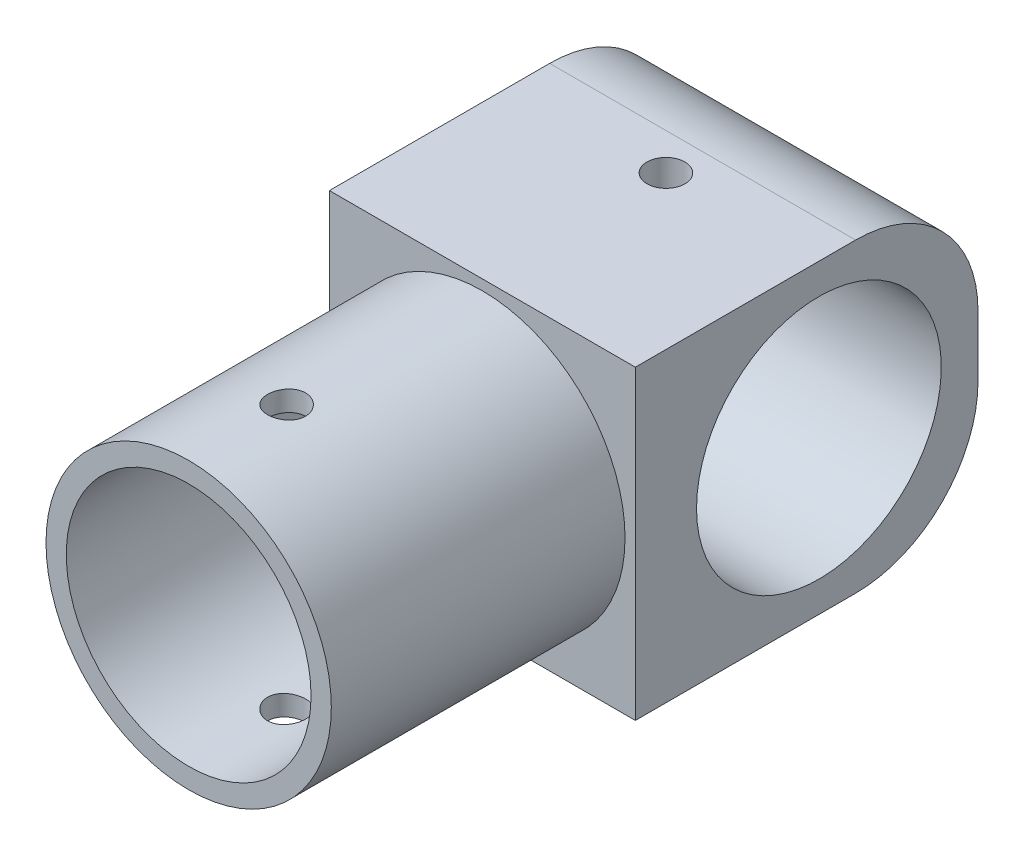
SolidWorks part; units mm, degrees
material "6061 合金"
ref_plane "前视基准面" through (0, 0, 0) normal (0, 0, 1) x (1, 0, 0)
ref_plane "上视基准面" through (0, 0, 0) normal (0, 1, 0) x (1, 0, 0)
ref_plane "右视基准面" through (0, 0, 0) normal (1, 0, 0) x (0, 0, -1)
other "Configuration Table"
ref_plane "基准面1" through (0, -5.2507, 0) normal (0, -1, 0) x (1, 0, 0)
sketch "草图1" plane through (0, -5.2507, 0) normal (0, -1, 0) x (1, 0, 0)
  line L0 (-8.6144, 0) -> (-8.6144, -28)
  line L1 (-8.6144, -28) -> (16.3856, -28)
  line L2 (16.3856, -28) -> (16.3856, 0)
  line L3 (16.3856, 0) -> (-8.6144, 0)
extrude "凸台-拉伸1" add sketch "草图1" against normal blind 25
ref_plane "基准面2" through (0, 7.2493, 0) normal (0, -1, 0) x (1, 0, 0)
sketch "草图2" plane through (0, 7.2493, 0) normal (0, -1, 0) x (1, 0, 0)
  line L0 (15.543, 24) -> (3.8856, 24)
  line L1 (3.8856, 24) -> (3.8856, 0)
  line L2 (3.8856, 0) -> (15.543, 0)
  line L3 (15.543, 0) -> (15.543, 24)
  line L4 (3.8856, 24) -> (3.8856, 0) construction
  dimension "D1" = 24
revolve "旋转1" add sketch "草图2" angle 360 about L4
hole_wizard "Ø20.0 (20) 直径孔1" positions "草图4" profile "草图3" hole size "Ø20.0" standard "ANSI Metric"
sketch "草图4" plane through (-8.6144, 0, 0) normal (-1, 0, 0) x (0, 0, 1)
  point P0 (-15, 7.2493)
sketch "草图3" plane through (-8.6144, 7.2493, -15) normal (0, 1, 0) x (0, 0, 1)
  line L0 (0, 0) -> (0, 25)
  line L1 (0, 25) -> (10, 25)
  line L2 (10, 25) -> (10, 0)
  line L5 (10, 0) -> (0, 0)
  line L11 (0, -6.35) -> (0, 107.95) construction
  dimension "通孔孔直径" = 20
  dimension "通孔孔深度" = 25
hole_wizard "Ø20.0 (20) 直径孔2" positions "草图6" profile "草图5" hole size "Ø20.0" standard "ANSI Metric"
sketch "草图6" plane through (0, 0, 24) normal (0, 0, 1) x (1, 0, 0)
  point P0 (3.8856, 7.2493)
sketch "草图5" plane through (3.8856, 7.2493, 24) normal (1, 0, 0) x (0, -1, 0)
  line L0 (0, 0) -> (0, 23)
  line L1 (0, 23) -> (10, 23)
  line L2 (10, 23) -> (10, 0)
  line L5 (10, 0) -> (0, 0)
  line L10 (0, 23) -> (-10, 23) construction
  line L11 (0, -6.35) -> (0, 107.95) construction
  dimension "孔直径" = 20
  dimension "孔深度" = 23
  dimension "导头角度" = 180
fillet "圆角1" radius 10 2 edges at (3.8856, -5.2507, -28) (3.8856, 19.7493, -28)
sketch "草图7" plane through (0, 7.2493, 0) normal (0, -1, 0) x (1, 0, 0)
  line L1 (15.543, 24) -> (-7.7718, 24) construction
  circle A0 centre (3.8856, 16) radius 1.55
  dimension "D1" = 3.1
  dimension "D2" = 8
  dimension "D3" = 10
extrude "切除-拉伸1" cut sketch "草图7" against normal through all and the other way through all
sketch "草图9" plane through (0, 19.7493, 0) normal (0, 1, 0) x (1, 0, 0)
  line L0 (16.3856, 18) -> (16.3856, 0) construction
  circle A0 centre (3.8856, 15) radius 1.55
  dimension "D1" = 3.1
  dimension "D2" = 12.5
  dimension "D3" = 10
extrude "切除-拉伸2" cut sketch "草图9" against normal through all
